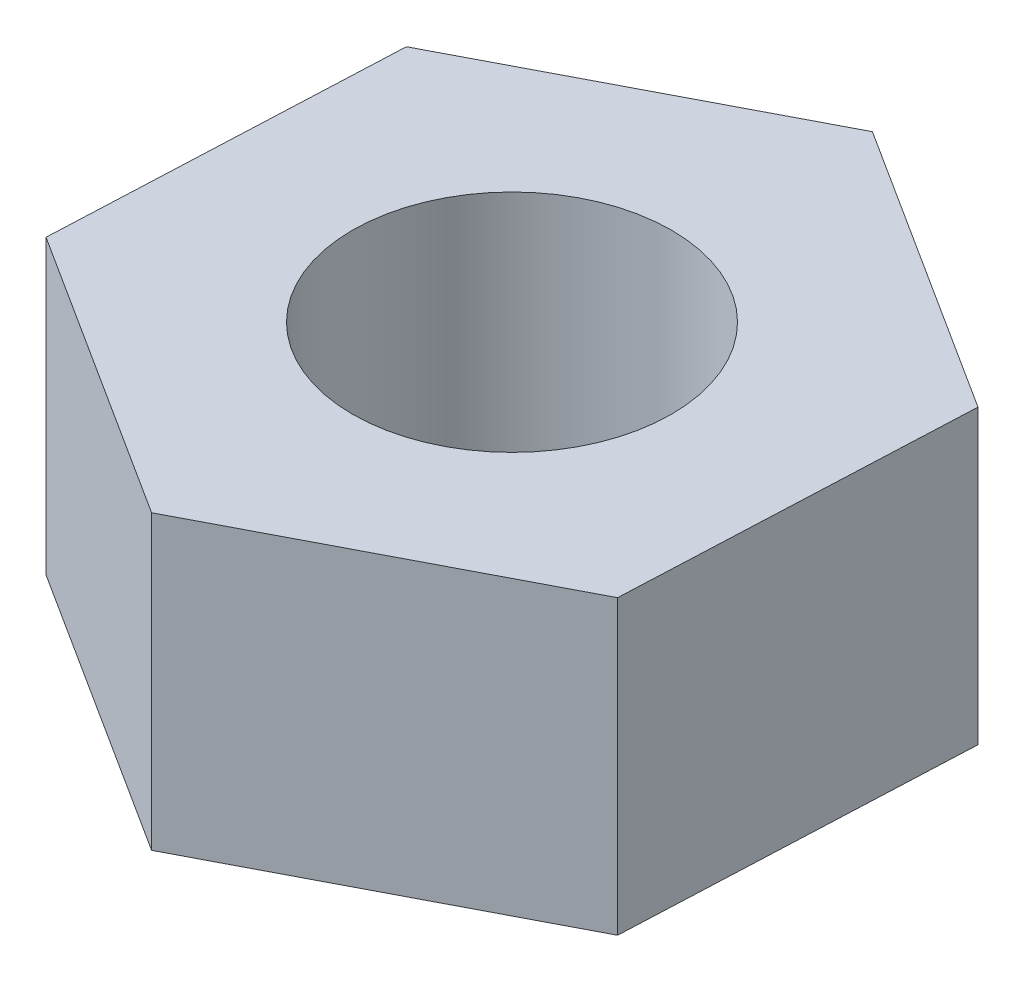
SolidWorks part; units mm, degrees
ref_plane "Front Plane" through (0, 0, 0) normal (0, 0, 1) x (1, 0, 0)
ref_plane "Top Plane" through (0, 0, 0) normal (0, 1, 0) x (1, 0, 0)
ref_plane "Right Plane" through (0, 0, 0) normal (1, 0, 0) x (0, 0, -1)
sketch "Sketch1" plane through (0, 0, 0) normal (0, 1, 0) x (1, 0, 0)
  line L1 (5.4808, -3.4944) -> (5.7666, 2.9993)
  line L2 (5.7666, 2.9993) -> (0.2858, 6.4937)
  line L3 (0.2858, 6.4937) -> (-5.4808, 3.4944)
  line L4 (-5.4808, 3.4944) -> (-5.7666, -2.9993)
  line L5 (-5.7666, -2.9993) -> (-0.2858, -6.4937)
  line L6 (-0.2858, -6.4937) -> (5.4808, -3.4944)
  circle A0 centre (0, 0) radius 5.6292 construction
extrude "Boss-Extrude1" add sketch "Sketch1" along normal blind 5.5
sketch "Sketch2" plane through (0, 5.5, 0) normal (0, 1, 0) x (1, 0, 0)
  circle A0 centre (0, 0) radius 3
extrude "Cut-Extrude1" cut sketch "Sketch2" against normal blind 5.5
